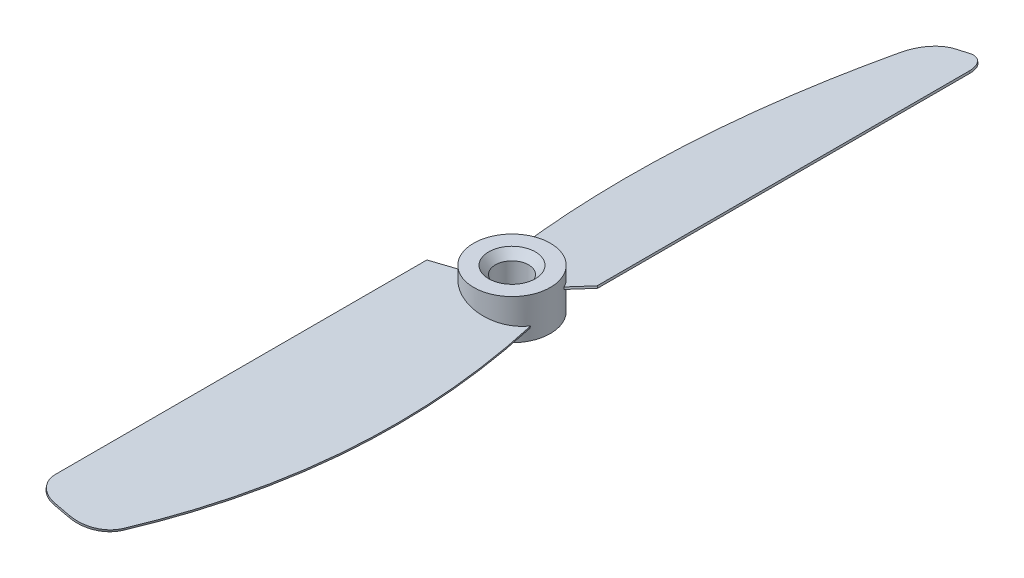
SolidWorks part; units mm, degrees
ref_plane "Front Plane" through (0, 0, 0) normal (0, 0, 1) x (1, 0, 0)
ref_plane "Top Plane" through (0, 0, 0) normal (0, 1, 0) x (1, 0, 0)
ref_plane "Right Plane" through (0, 0, 0) normal (1, 0, 0) x (0, 0, -1)
sketch "Sketch1" plane through (0, 0, 0) normal (0, 1, 0) x (1, 0, 0)
  circle A0 centre (0, 0) radius 5.75
  dimension "D1" = 11.5
extrude "Boss-Extrude1" add sketch "Sketch1" along normal mid plane 6
sketch "Sketch2" plane through (0, 0, 0) normal (0, 0, 1) x (1, 0, 0)
  line L0 (-5.75, 1.3275) -> (5.9895, -1.3828) construction
  line L1 (-5.75, 3) -> (-5.75, -3) construction
  line L3 (-5.75, -3) -> (5.75, -3) construction
  dimension "D1" = 13
ref_plane "Plane1" through (0, 0, 0) normal (-0.225, -0.9744, 0) x (0.9744, -0.225, 0)
sketch "Sketch3" plane through (0, 0, 0) normal (-0.225, -0.9744, 0) x (0.9744, -0.225, 0)
  line L0 (-4.4547, 2.3124) -> (-8.3104, 4.7052)
  line L1 (-8.3104, 4.7052) -> (-8.3104, 60.5)
  line L2 (-5.3104, 63.5) -> (-2.9617, 63.5)
  arc A0 (1.8165, 59.9727) -> (-2.9617, 63.5) centre (-2.9617, 58.5) ccw
  arc A1 (-8.3104, 60.5) -> (-5.3104, 63.5) centre (-5.3104, 60.5) cw
  ellipse E0 centre (0.6749, 0) end of major axis (0.6749, 5.75) minor radius 5.6026 construction
  spline S0 degree 2 poles (-4.4547, 2.3124) (0.1945, 8.9416) (5.0076, 0.8481) knots 0 0 0 1 1 1
  spline S1 degree 2 poles (1.8165, 59.9727) (11.3054, 30.9061) (5.0076, 0.8481) knots 0 0 0 1 1 1
  dimension "D2" = 5
  dimension "D3" = 3
  dimension "D1" = 63.5
extrude "Boss-Extrude2" add sketch "Sketch3" along normal mid plane 0.3
pattern_circular "CirPattern1" count 2 over 360 about axis through (0, -3, 0) along (0, 1, 0) of "Boss-Extrude2"
sketch "Sketch4" plane through (0, 3, 0) normal (0, 1, 0) x (1, 0, 0)
  circle A0 centre (0, 0) radius 2.5
  dimension "D1" = 5
extrude "Cut-Extrude1" cut sketch "Sketch4" against normal through all
chamfer "Chamfer1" distance 1 angle 50 2 edges at (0, 3, 2.5) (0, -3, 2.5)
